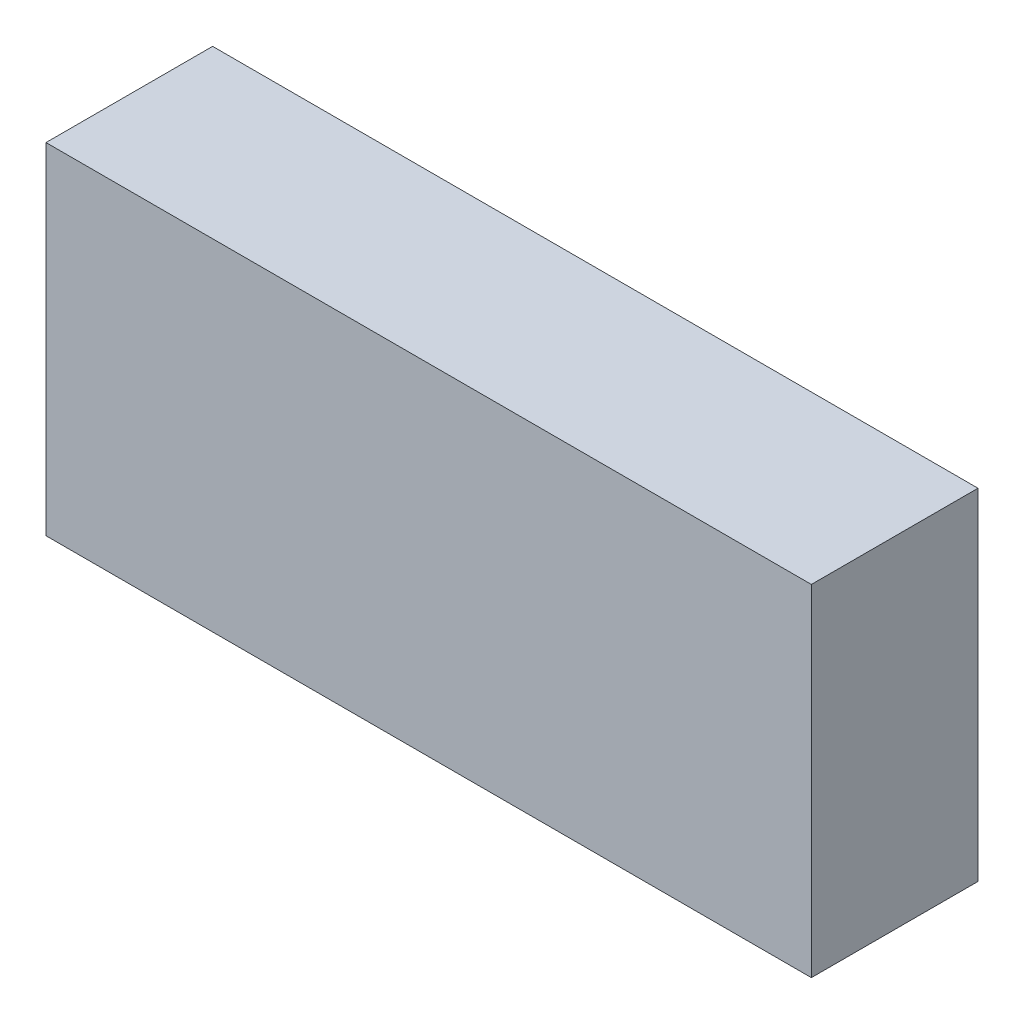
SolidWorks part; units mm, degrees
ref_plane "Plan de face" through (0, 0, 0) normal (0, 0, 1) x (1, 0, 0)
ref_plane "Plan de dessus" through (0, 0, 0) normal (0, 1, 0) x (1, 0, 0)
ref_plane "Plan de droite" through (0, 0, 0) normal (1, 0, 0) x (0, 0, -1)
sketch "Esquisse1" plane through (0, 0, 0) normal (0, 0, 1) x (1, 0, 0)
  line L1 (0, 0) -> (45.9319, 0)
  line L2 (0, 0) -> (0, -20.4371)
  line L3 (0, -20.4371) -> (45.9319, -20.4371)
  line L4 (45.9319, 0) -> (45.9319, -20.4371)
extrude "Boss.-Extru.1" add sketch "Esquisse1" along normal blind 10
